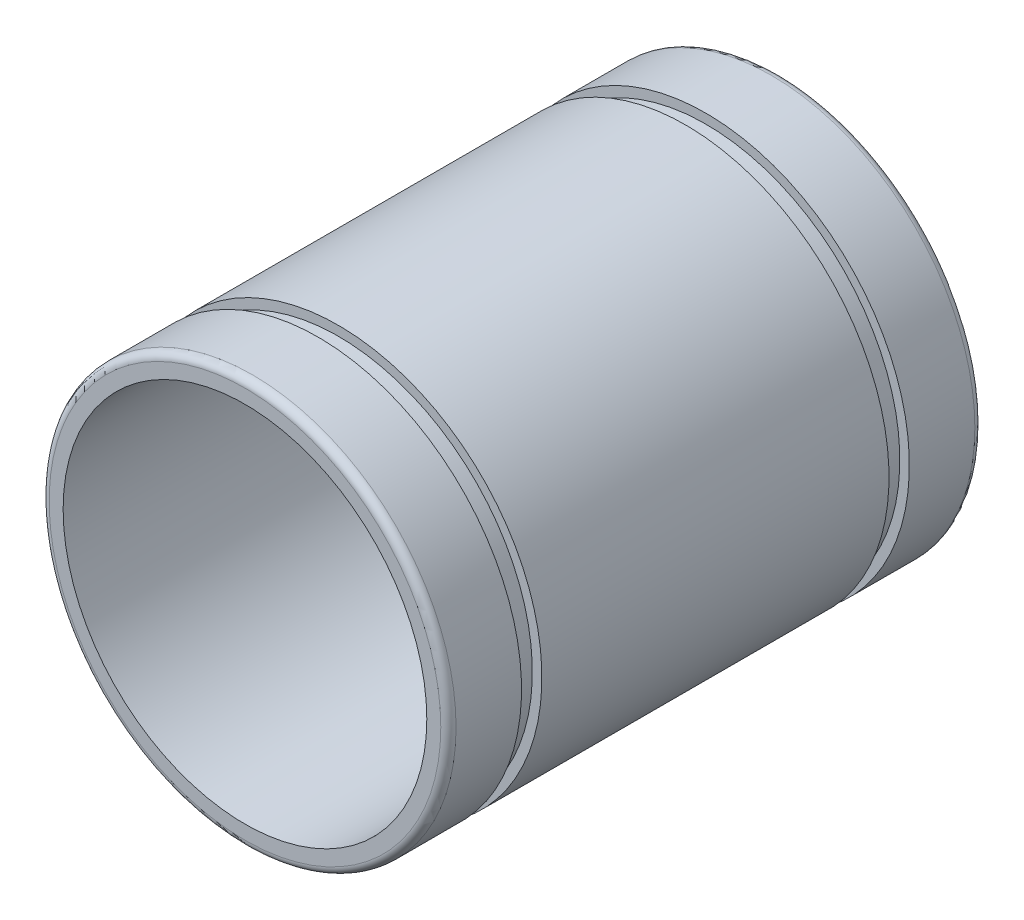
SolidWorks part; units mm, degrees
ref_plane "Front Plane" through (0, 0, 0) normal (0, 0, 1) x (1, 0, 0)
ref_plane "Top Plane" through (0, 0, 0) normal (0, 1, 0) x (1, 0, 0)
ref_plane "Right Plane" through (0, 0, 0) normal (1, 0, 0) x (0, 0, -1)
sketch "Sketch1" plane through (0, 0, 0) normal (0, 0, 1) x (1, 0, 0)
  circle A0 centre (0, 0) radius 16
  circle A1 centre (0, 0) radius 14.3
  dimension "D1" = 32
  dimension "D2" = 28.6
extrude "Boss-Extrude1" add sketch "Sketch1" along normal blind 42
sketch "Sketch3" plane through (0, 0, 0) normal (0, 1, 0) x (1, 0, 0)
  line L0 (0, 0) -> (0, -42) construction
  line L1 (-16, -42) -> (16, -42) construction
  line L2 (16, 0) -> (16, -42) construction
  line L3 (0, -21) -> (16, -21) construction
  line L4 (16, -34.65) -> (15.25, -34.65)
  line L5 (16, -5.75) -> (15.25, -5.75)
  line L6 (16, -5.75) -> (16, -7.35)
  line L7 (16, -7.35) -> (15.25, -7.35)
  line L8 (15.25, -5.75) -> (15.25, -7.35)
  line L9 (16, -36.25) -> (16, -34.65)
  line L10 (16, -36.25) -> (15.25, -36.25)
  line L11 (15.25, -36.25) -> (15.25, -34.65)
  dimension "D1" = 16
  dimension "D2" = 1.6
  dimension "D3" = 0.75
  dimension "D4" = 30.5
revolve "Cut-Revolve2" cut sketch "Sketch3" angle 360 about L0
fillet "Fillet1" radius 0.6 2 edges at (16, 0, 0) (16, 0, 42)
